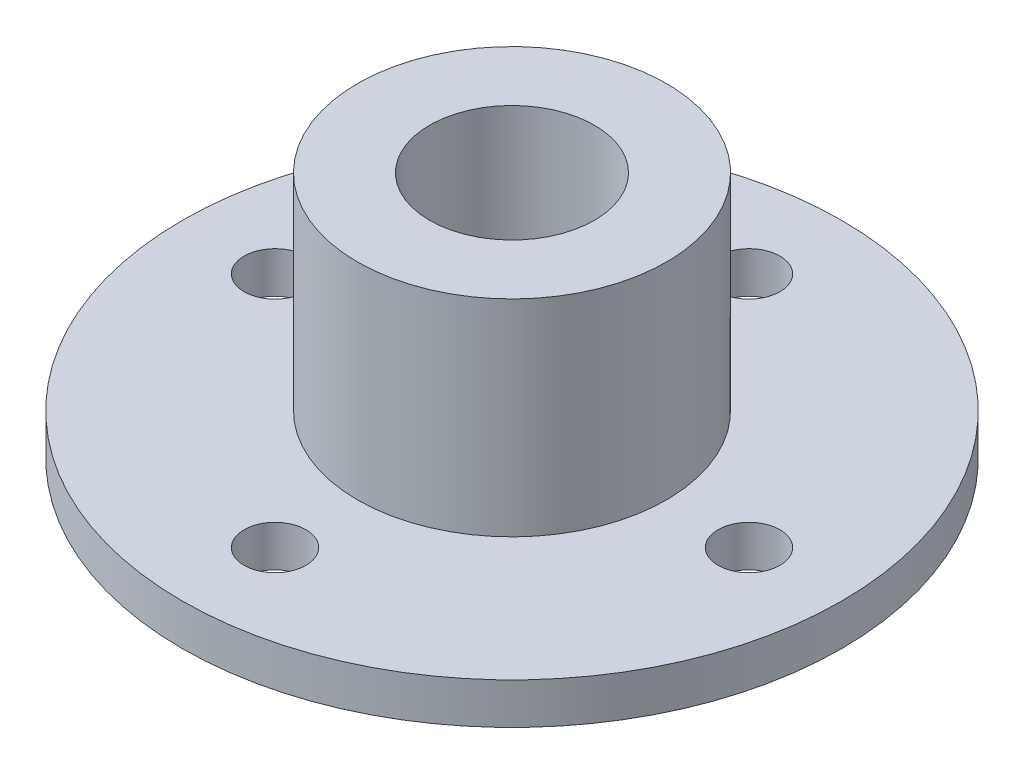
SolidWorks part; units mm, degrees
ref_plane "前视基准面" through (0, 0, 0) normal (0, 0, 1) x (1, 0, 0)
ref_plane "上视基准面" through (0, 0, 0) normal (0, 1, 0) x (1, 0, 0)
ref_plane "右视基准面" through (0, 0, 0) normal (1, 0, 0) x (0, 0, -1)
sketch "草图1" plane through (0, 0, 0) normal (0, 1, 0) x (1, 0, 0)
  line L0 (-60.9993, 0) -> (60.9993, 0) construction
  line L1 (0, 50.3274) -> (0, -50.3274) construction
  circle A0 centre (0, 0) radius 16
  point P4 (0, 0)
  point P8 (0, 0)
  dimension "D1" = 32
extrude "凸台-拉伸1" add sketch "草图1" along normal blind 2
sketch "草图2" plane through (0, 2, 0) normal (0, 1, 0) x (1, 0, 0)
  circle A0 centre (0, 0) radius 7.5
  circle A1 centre (0, 0) radius 4
  dimension "D1" = 15
  dimension "D2" = 8
extrude "凸台-拉伸2" add sketch "草图2" along normal blind 10
sketch "草图3" plane through (0, 2, 0) normal (0, 1, 0) x (1, 0, 0)
  line L0 (25.1788, 0) -> (-25.1788, 0) construction
  line L1 (0, 17.9418) -> (0, -17.9418) construction
  circle A0 centre (0, 0) radius 11.5 construction
  circle A1 centre (-11.5, 0) radius 1.5
  circle A2 centre (0, 11.5) radius 1.5
  circle A3 centre (11.5, 0) radius 1.5
  circle A4 centre (0, -11.5) radius 1.5
  point P6 (0, 0)
  point P9 (0, 0)
  point P20 (0, 0)
  dimension "D1" = 23
  dimension "D2" = 3
  dimension "D3" = 4
extrude "切除-拉伸1" cut sketch "草图3" against normal blind 10
